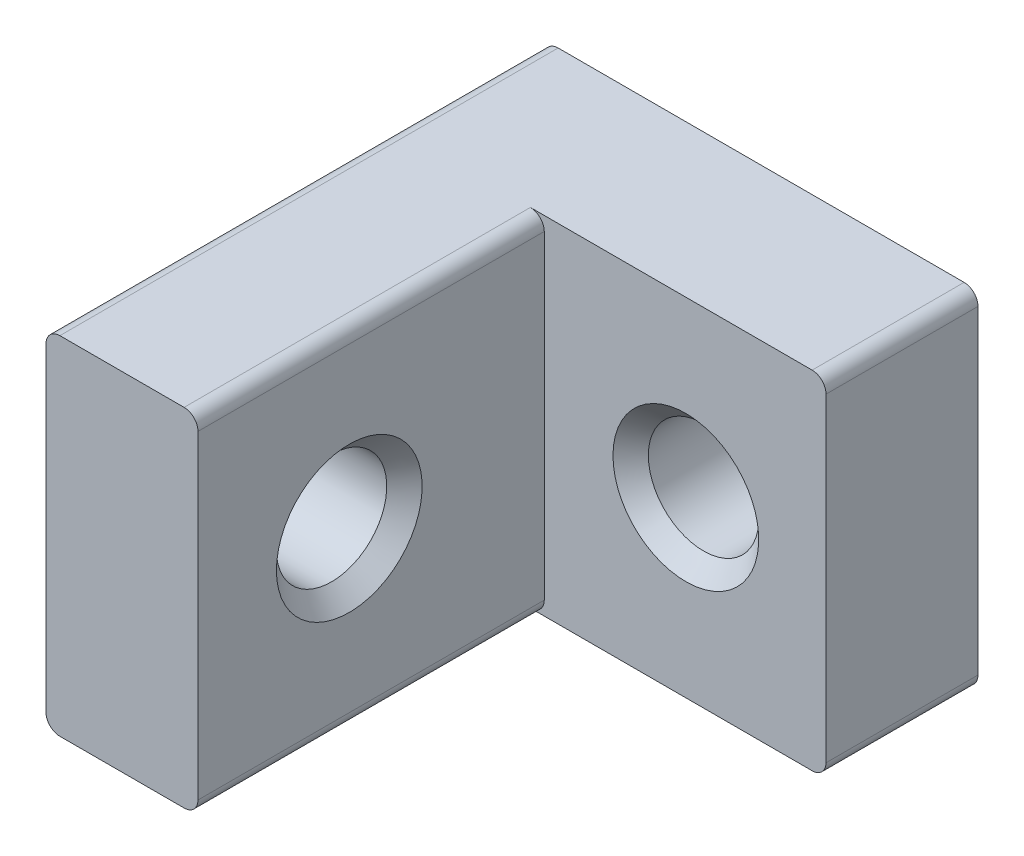
SolidWorks part; units mm, degrees
material "Copper"
ref_plane "PL-01 Front" through (0, 0, 0) normal (0, 0, 1) x (1, 0, 0)
ref_plane "PL-02 Top" through (0, 0, 0) normal (0, 1, 0) x (1, 0, 0)
ref_plane "PL-03 Right" through (0, 0, 0) normal (1, 0, 0) x (0, 0, -1)
sketch "Sketch1" plane through (0, 0, 0) normal (0, 1, 0) x (1, 0, 0)
  line L0 (5.9436, -18.2372) -> (5.9436, -5.5626)
  line L1 (0.381, 0) -> (16.256, 0)
  line L2 (0.381, 0) -> (0.381, -18.2372)
  line L3 (0.381, -18.2372) -> (5.9436, -18.2372)
  line L4 (16.256, 0) -> (16.256, -5.5626)
  line L5 (5.9436, -5.5626) -> (16.256, -5.5626)
  circle A0 centre (7.1662, -6.8619) radius 11.1125 construction
  dimension "D6" = 22.225
  dimension "D1" = 0.381
  dimension "D2" = 15.875
  dimension "D3" = 18.2372
  dimension "D4" = 5.5626
  dimension "D5" = 5.5626
extrude "Extrude1" add sketch "Sketch1" along normal mid plane 12.7
hole_wizard "#10-32 Tapped Hole2" positions "Sketch3" profile "Sketch2" tap size "#10-32" standard "Ansi Inch" end condition up to next
sketch "Sketch3" plane through (0.381, 0, 0) normal (-1, 0, 0) x (0, 0, 1)
  point P0 (12.7, 0)
  dimension "D1" = 12.7
sketch "Sketch2" plane through (0.381, 0, 12.7) normal (0, 1, 0) x (0, 0, 1)
  line L0 (0, 0) -> (0, 5.5626)
  line L1 (0, 5.5626) -> (2.667, 5.5626)
  line L2 (2.0193, 4.9149) -> (2.0193, 0.6477)
  line L3 (2.0193, 0.6477) -> (2.667, 0)
  line L5 (2.667, 0) -> (0, 0)
  line L6 (-2.0193, 0.6477) -> (-2.667, 0) construction
  line L7 (2.667, 5.5626) -> (2.0193, 4.9149)
  line L8 (-2.667, 5.5626) -> (-2.0193, 4.9149) construction
  line L11 (0, -6.35) -> (0, 107.95) construction
  dimension "Thread Major Dia." = 4.0386
  dimension "Thru Tap Drill Depth" = 5.5626
  dimension "Near C'Sink Dia." = 5.334
  dimension "Near C'Sink Angle" = 90
  dimension "Far C'Sink Dia." = 5.334
  dimension "Far C'Sink Angle" = 90
hole_wizard "#10-32 Tapped Hole1" positions "Sketch5" profile "Sketch4" tap size "#10-32" standard "Ansi Inch" end condition up to next
sketch "Sketch5" plane through (0, 0, 0) normal (0, 0, -1) x (-1, 0, 0)
  point P0 (-11.1252, 0)
  dimension "D1" = 10.7442
sketch "Sketch4" plane through (11.1252, 0, 0) normal (1, 0, 0) x (0, 1, 0)
  line L0 (0, 0) -> (0, 5.5626)
  line L1 (0, 5.5626) -> (2.667, 5.5626)
  line L2 (2.0193, 4.9149) -> (2.0193, 0.6477)
  line L3 (2.0193, 0.6477) -> (2.667, 0)
  line L5 (2.667, 0) -> (0, 0)
  line L6 (-2.0193, 0.6477) -> (-2.667, 0) construction
  line L7 (2.667, 5.5626) -> (2.0193, 4.9149)
  line L8 (-2.667, 5.5626) -> (-2.0193, 4.9149) construction
  line L11 (0, -6.35) -> (0, 107.95) construction
  dimension "Thread Major Dia." = 4.0386
  dimension "Thru Tap Drill Depth" = 5.5626
  dimension "Near C'Sink Dia." = 5.334
  dimension "Near C'Sink Angle" = 90
  dimension "Far C'Sink Dia." = 5.334
  dimension "Far C'Sink Angle" = 90
fillet "Fillet1" radius 0.508 6 edges at (16.256, -6.35, 2.7813) (16.256, 6.35, 2.7813) (5.9436, -6.35, 11.8999) (5.9436, 6.35, 11.8999) (0.381, -6.35, 9.1186) (0.381, 6.35, 9.1186)
pattern_linear "LPattern1" [suppressed] count 6 spacing 22.606
